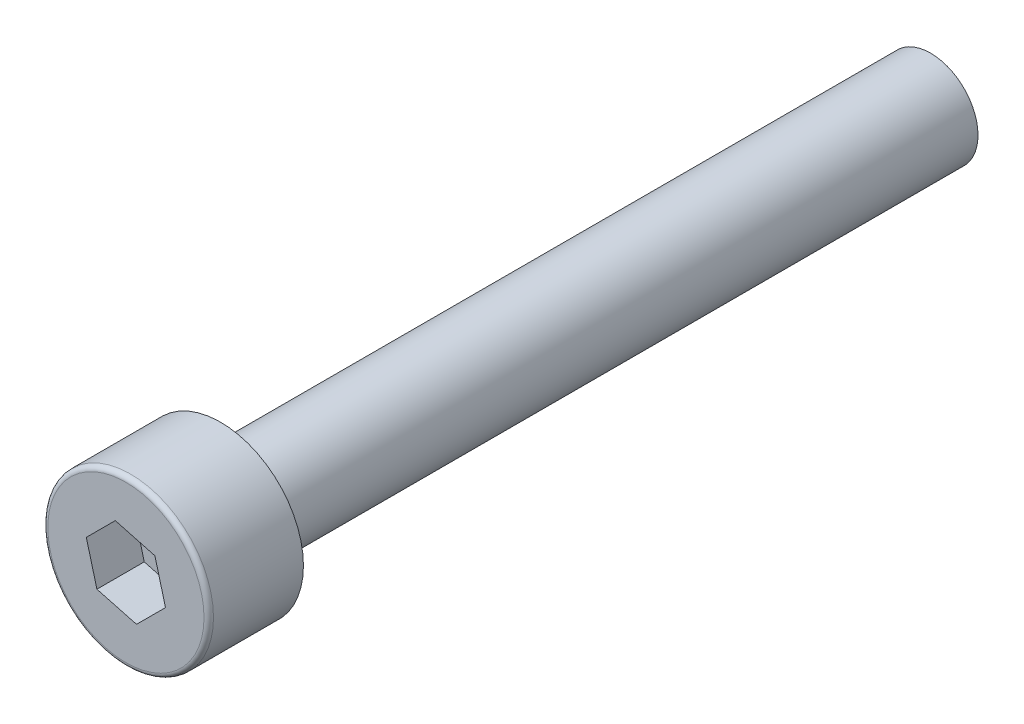
SolidWorks part; units mm, degrees
ref_plane "前视基准面" through (0, 0, 0) normal (0, 0, 1) x (1, 0, 0)
ref_plane "上视基准面" through (0, 0, 0) normal (0, 1, 0) x (1, 0, 0)
ref_plane "右视基准面" through (0, 0, 0) normal (1, 0, 0) x (0, 0, -1)
sketch "草图1" plane through (0, 0, 0) normal (0, 0, 1) x (1, 0, 0)
  circle A0 centre (0, 0) radius 3.5
  dimension "D1" = 7
extrude "凸台-拉伸1" add sketch "草图1" along normal blind 4
sketch "草图2" plane through (0, 0, 4) normal (0, 0, 1) x (1, 0, 0)
  line L1 (-1.2247, -1.2247) -> (0.4483, -1.673)
  line L2 (0.4483, -1.673) -> (1.673, -0.4483)
  line L3 (1.673, -0.4483) -> (1.2247, 1.2247)
  line L4 (1.2247, 1.2247) -> (-0.4483, 1.673)
  line L5 (-0.4483, 1.673) -> (-1.673, 0.4483)
  line L6 (-1.673, 0.4483) -> (-1.2247, -1.2247)
  circle A0 centre (0, 0) radius 1.5 construction
  dimension "D1" = 3
extrude "切除-拉伸1" cut sketch "草图2" against normal blind 2
sketch "草图3" plane through (0, 0, 0) normal (0, 0, -1) x (-1, 0, 0)
  circle A0 centre (0, 0) radius 2
  dimension "D1" = 4
extrude "凸台-拉伸2" add sketch "草图3" along normal blind 30
fillet "圆角1" radius 0.2 1 edges at (3.5, 0, 4)
